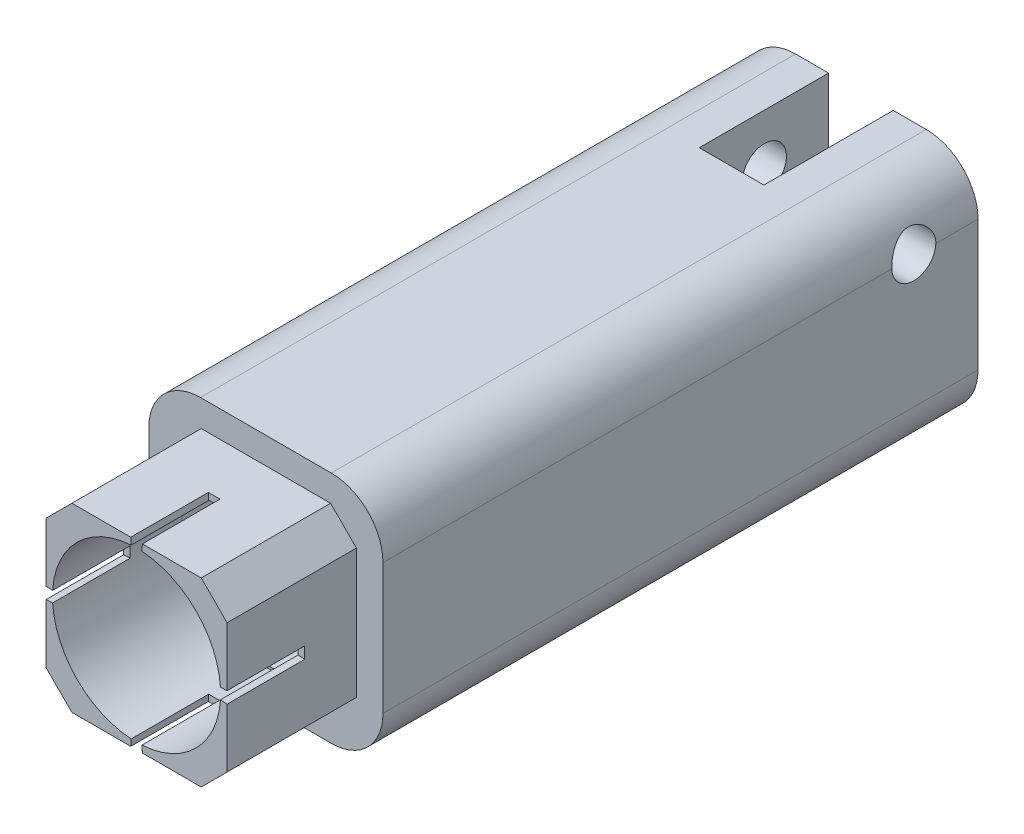
SolidWorks part; units mm, degrees
ref_plane "Front Plane" through (0, 0, 0) normal (0, 0, 1) x (1, 0, 0)
ref_plane "Top Plane" through (0, 0, 0) normal (0, 1, 0) x (1, 0, 0)
ref_plane "Right Plane" through (0, 0, 0) normal (1, 0, 0) x (0, 0, -1)
sketch "Sketch1" plane through (0, 0, 0) normal (0, 0, 1) x (1, 0, 0)
  line L0 (-5.05, 9.05) -> (5.05, 9.05)
  line L1 (9.05, -5.05) -> (9.05, 5.05)
  line L2 (0, 0) -> (0, 14.1446) construction
  line L3 (-9.05, -5.05) -> (-9.05, 5.05)
  line L4 (-12.732, 0) -> (15.0845, 0) construction
  line L5 (-5.05, -9.05) -> (5.05, -9.05)
  arc A4 (5.05, 9.05) -> (9.05, 5.05) centre (5.05, 5.05) cw
  arc A5 (9.05, -5.05) -> (5.05, -9.05) centre (5.05, -5.05) cw
  arc A6 (-5.05, -9.05) -> (-9.05, -5.05) centre (-5.05, -5.05) cw
  arc A7 (-9.05, 5.05) -> (-5.05, 9.05) centre (-5.05, 5.05) cw
  point P11 (9.05, 0)
  point P12 (0, 9.05)
  point P20 (0, -9.05)
  point P21 (-9.05, 0)
  dimension "D3" = 0
  dimension "D1" = 5.05
  dimension "D2" = 5.05
  dimension "D4" = 9.05
  dimension "D5" = 9.05
extrude "Boss-Extrude1" add sketch "Sketch1" along normal blind 46
sketch "Sketch3" plane through (0, 0, 46) normal (0, 0, 1) x (1, 0, 0)
  line L0 (-5, -7) -> (5, -7)
  line L1 (-7, -5) -> (-7, 5)
  line L2 (-5, 7) -> (5, 7)
  line L3 (7, -5) -> (7, 5)
  line L4 (-7, -7) -> (7, 7) construction
  line L5 (-7, 7) -> (7, -7) construction
  line L6 (5, 7) -> (7, 5)
  line L7 (-5, 7) -> (-7, 5)
  line L8 (-7, -5) -> (-5, -7)
  line L9 (5, -7) -> (7, -5)
  circle A6 centre (0, 0) radius 6.5
  point P3 (0, 0)
  dimension "D1" = 14
  dimension "D3" = 13
  dimension "D4" = 0
  dimension "D5" = 0
  dimension "D6" = 0
extrude "Boss-Extrude2" add sketch "Sketch3" along normal blind 10
sketch "Sketch11" plane through (0, 0, 56) normal (0, 0, 1) x (1, 0, 0)
  line L0 (0, 0) -> (7, 0.45)
  line L1 (7, -5) -> (7, 5) construction
  line L2 (7, 0.45) -> (7, -0.45)
  line L3 (7, -0.45) -> (0, 0)
  dimension "D1" = 0.45
  dimension "D2" = 0.45
extrude "Cut-Extrude7" cut sketch "Sketch11" against normal blind 6
pattern_circular "CirPattern1" count 4 over 360 about axis through (0, 0, 56) along (0, 0, -1) of "Cut-Extrude7"
sketch "Sketch12" plane through (0, 0, 46) normal (0, 0, 1) x (1, 0, 0)
  line L0 (0, 0) -> (0, 14.1446) construction
  circle A0 centre (0, 0.1925) radius 6.5
  dimension "D1" = 13
extrude "Cut-Extrude8" cut sketch "Sketch12" against normal blind 30
sketch "Sketch13" plane through (0, 0, 0) normal (0, 0, 1) x (1, 0, 0)
  line L0 (-12.732, 0) -> (15.0845, 0) construction
  line L3 (-2.5, 0) -> (-2.5, 9.05)
  line L4 (-5.05, 9.05) -> (5.05, 9.05) construction
  line L5 (-2.5, 9.05) -> (2.5, 9.05)
  line L6 (2.5, 9.05) -> (2.5, 0)
  arc A0 (-2.5, 0) -> (2.5, 0) centre (0, 0) ccw
  dimension "D2" = 2.5
  dimension "D1" = 0
extrude "Cut-Extrude9" cut sketch "Sketch13" along normal blind 10
sketch "Sketch14" plane through (0, 0, 0) normal (1, 0, 0) x (0, 0, -1)
  circle A0 centre (-4.9636, 5.105) radius 1.705
  dimension "D1" = 3.41
  dimension "D2" = 5.105
extrude "Cut-Extrude10" cut sketch "Sketch14" against normal mid plane 25
